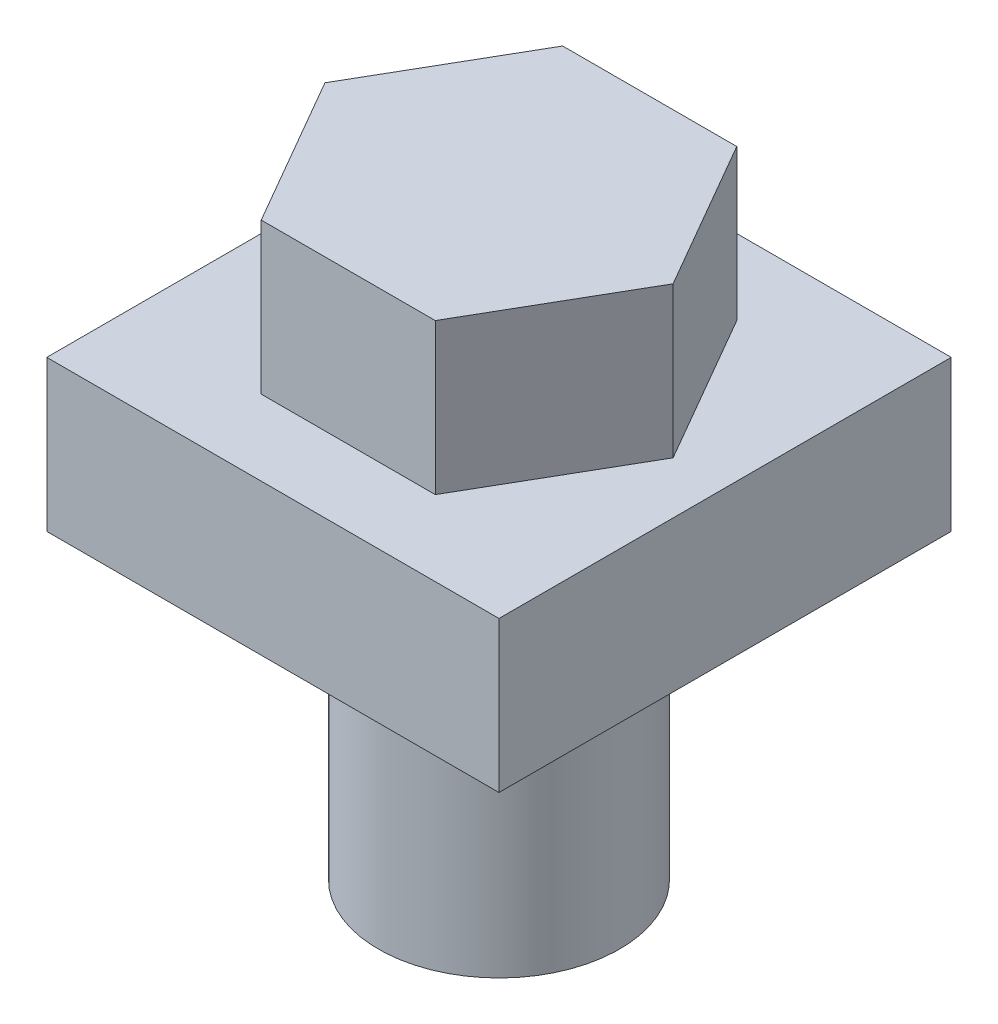
SolidWorks part; units mm, degrees
ref_plane "Front Plane" through (0, 0, 0) normal (0, 0, 1) x (1, 0, 0)
ref_plane "Top Plane" through (0, 0, 0) normal (0, 1, 0) x (1, 0, 0)
ref_plane "Right Plane" through (0, 0, 0) normal (1, 0, 0) x (0, 0, -1)
sketch "Sketch1" plane through (0, 0, 0) normal (0, 1, 0) x (1, 0, 0)
  line L1 (7.5, -7.5) -> (-7.5, -7.5)
  line L2 (7.5, -7.5) -> (7.5, 7.5)
  line L3 (7.5, 7.5) -> (-7.5, 7.5)
  line L4 (-7.5, -7.5) -> (-7.5, 7.5)
  line L5 (7.5, -7.5) -> (-7.5, 7.5) construction
  line L6 (7.5, 7.5) -> (-7.5, -7.5) construction
  point P0 (0, 0)
  dimension "D1" = 15
  dimension "D2" = 15
extrude "Boss-Extrude1" add sketch "Sketch1" along normal blind 5
sketch "Sketch2" plane through (0, 5, 0) normal (0, 1, 0) x (1, 0, 0)
  line L1 (-2.8868, 5) -> (-5.7735, 0)
  line L2 (-5.7735, 0) -> (-2.8868, -5)
  line L3 (-2.8868, -5) -> (2.8868, -5)
  line L4 (2.8868, -5) -> (5.7735, 0)
  line L5 (5.7735, 0) -> (2.8868, 5)
  line L6 (2.8868, 5) -> (-2.8868, 5)
  circle A0 centre (0, 0) radius 5 construction
  dimension "D1" = 10
extrude "Boss-Extrude2" add sketch "Sketch2" along normal blind 5
sketch "Sketch3" plane through (0, 0, 0) normal (0, -1, 0) x (1, 0, 0)
  circle A0 centre (0, 0) radius 4
  dimension "D1" = 8
extrude "Boss-Extrude3" add sketch "Sketch3" along normal blind 10
equation "\"Indenter_height\"= 5mm"
equation "\"Side_base\"= 15mm"
equation "\"Side_Thickness\"= 5mm"
equation "\"Connector_height\"= 10mm"
equation "\"Connector_Dia\"= 8mm"
equation "\"Indenter_dia\"= 10mm"
equation "\"D2@Sketch1\"=\"Side_base\""
equation "\"D1@Sketch1\"=\"Side_base\""
equation "\"D1@Boss-Extrude2\"=\"Indenter_height\""
equation "\"D1@Sketch2\"=\"Indenter_dia\""
equation "\"D1@Boss-Extrude1\"=\"Side_Thickness\""
equation "\"D1@Boss-Extrude3\"=\"Connector_height\""
equation "\"D1@Sketch3\"=\"Connector_Dia\""
